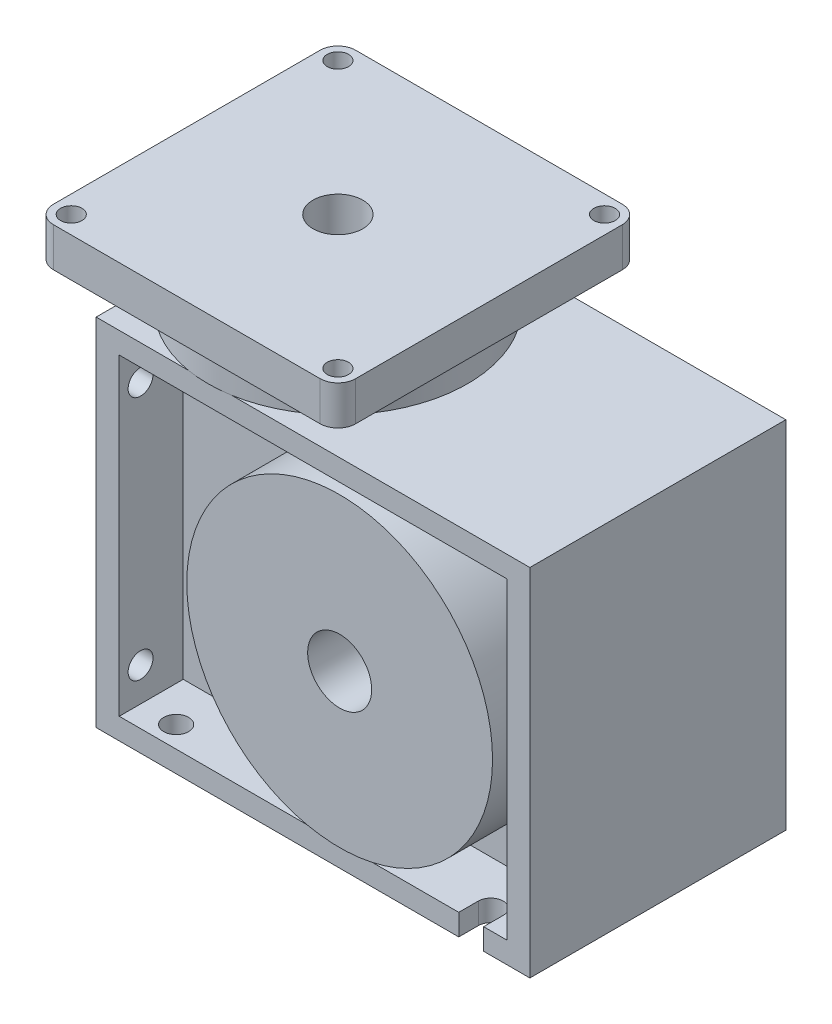
SolidWorks part; units mm, degrees
ref_plane "Alzado" through (0, 0, 0) normal (0, 0, 1) x (1, 0, 0)
ref_plane "Planta" through (0, 0, 0) normal (0, 1, 0) x (1, 0, 0)
ref_plane "Vista lateral" through (0, 0, 0) normal (1, 0, 0) x (0, 0, -1)
sketch "Croquis2" plane through (0, 0, 0) normal (0, 1, 0) x (1, 0, 0)
  line L1 (-61, 36) -> (61, 36)
  line L2 (-61, 36) -> (-61, -36)
  line L3 (-61, -36) -> (61, -36)
  line L4 (61, 36) -> (61, -36)
  point P0 (0, 0)
  dimension "D1" = 122
  dimension "D2" = 72
extrude "Saliente-Extruir1" add sketch "Croquis2" along normal blind 100
sketch "Croquis3" plane through (0, 0, -36) normal (0, 0, -1) x (-1, 0, 0)
  line L0 (-61, 50) -> (61, 50) construction
  line L1 (-61, 100) -> (-61, 0) construction
  line L2 (61, 100) -> (61, 0) construction
  line L3 (0, 100) -> (0, 0) construction
  line L4 (-61, 100) -> (61, 100) construction
  line L6 (-54.5, 6) -> (54.5, 6)
  line L7 (-54.5, 6) -> (-54.5, 94)
  line L8 (-54.5, 94) -> (54.5, 94)
  line L9 (54.5, 6) -> (54.5, 94)
  point P11 (0, 50)
  dimension "D1" = 88
  dimension "D2" = 109
extrude "Cortar-Extruir1" cut sketch "Croquis3" against normal blind 18 contours L7 L6 L9 L8
sketch "Croquis4" plane through (0, 0, 36) normal (0, 0, 1) x (1, 0, 0)
  line L0 (-61, 50) -> (61, 50) construction
  line L1 (-61, 100) -> (-61, 0) construction
  line L2 (61, 100) -> (61, 0) construction
  line L3 (0, 100) -> (0, 0) construction
  line L4 (-61, 100) -> (61, 100) construction
  line L6 (-54.5, 6) -> (54.5, 6)
  line L7 (-54.5, 6) -> (-54.5, 94)
  line L8 (-54.5, 94) -> (54.5, 94)
  line L9 (54.5, 6) -> (54.5, 94)
  point P11 (0, 50)
  dimension "D1" = 88
  dimension "D2" = 109
extrude "Cortar-Extruir2" cut sketch "Croquis4" against normal blind 18
sketch "Croquis5" plane through (0, 100, 0) normal (0, 1, 0) x (1, 0, 0)
  line L0 (-61, 0) -> (7.5, 0) construction
  line L1 (-61, 36) -> (-61, -36) construction
  line L3 (-61, 0) -> (-29, 0)
  circle A0 centre (-29, 0) radius 36.5
  line M3 (61, 36) -> (-61, 36)
  line M4 (-61, 36) -> (-61, -36)
  line M5 (-61, -36) -> (61, -36)
  dimension "D2" = 73
  dimension "D1" = 32
extrude "Saliente-Extruir2" add sketch "Croquis5" along normal blind 12 contours L3 L0 A0 M3 M4 | A0 M4 | L0 L3 A0 M4 M5 | A0 M5 | A0 M3
sketch "Croquis6" plane through (0, 112, 0) normal (0, 1, 0) x (1, 0, 0)
  line L0 (-65.5, 0) -> (7.5, 0) construction
  line L1 (-29, 36.5) -> (-29, -36.5) construction
  line L3 (-71.5, -42.5) -> (13.5, -42.5)
  line L4 (-71.5, -42.5) -> (-71.5, 42.5)
  line L5 (-71.5, 42.5) -> (13.5, 42.5)
  line L6 (13.5, -42.5) -> (13.5, 42.5)
  circle A0 centre (-29, 0) radius 36.5 construction
  arc A1 (-22.9792, -36) -> (-22.9792, 36) centre (-29, 0) ccw construction
  point P10 (-29, 0)
  dimension "D1" = 85
  dimension "D2" = 85
extrude "Saliente-Extruir3" add sketch "Croquis6" along normal blind 11
sketch "Croquis7" plane through (0, 0, 18) normal (0, 0, 1) x (1, 0, 0)
  line L0 (-54.5, 50) -> (-33.5, 50)
  line L1 (-54.5, 94) -> (-54.5, 6) construction
  circle A1 centre (9.5, 50) radius 43
  dimension "D2" = 86
  dimension "D1" = 21
extrude "Saliente-Extruir7" add sketch "Croquis7" along normal blind 20 contours A1
sketch "Croquis8" plane through (0, 0, -18) normal (0, 0, -1) x (-1, 0, 0)
  line L0 (54.5, 50) -> (33.5, 50)
  line L1 (54.5, 6) -> (54.5, 94) construction
  circle A0 centre (-9.5, 50) radius 43
  dimension "D2" = 86
  dimension "D1" = 21
extrude "Saliente-Extruir8" add sketch "Croquis8" along normal blind 20 contours A0
sketch "Croquis9" plane through (0, 0, 38) normal (0, 0, 1) x (1, 0, 0)
  circle A0 centre (9.5, 50) radius 9
  dimension "D1" = 18
extrude "Cortar-Extruir3" cut sketch "Croquis9" against normal up to surface (76 mm away) up to face at (-33.5, 50, -38)
sketch "Croquis10" plane through (0, 0, 0) normal (0, -1, 0) x (1, 0, 0)
  line L0 (-48, 30) -> (-61, 30)
  line L2 (-61, -36) -> (-61, 36) construction
  line L4 (-44.5, 33.5) -> (-44.5, 36)
  line L6 (-61, 36) -> (61, 36) construction
  line L7 (-48, -30) -> (-61, -30)
  line L9 (-44.5, -33.5) -> (-44.5, -36)
  line L10 (61, -36) -> (-61, -36) construction
  line L17 (48, 30.5) -> (61, 30.5)
  line L18 (61, 36) -> (61, -36) construction
  line L19 (48, -30.5) -> (61, -30.5)
  line L21 (41, -30.5) -> (41, -36)
  line L22 (48, -30.5) -> (48, -36)
  line L23 (48, -36) -> (41, -36)
  line L24 (41, 30.5) -> (41, 36)
  line L25 (48, 30.5) -> (48, 36)
  line L26 (41, 36) -> (48, 36)
  circle A4 centre (-44.5, 30) radius 3.5
  circle A5 centre (-44.5, -30) radius 3.5
  arc A6 (41, 30.5) -> (48, 30.5) centre (44.5, 30.5) ccw
  arc A7 (48, -30.5) -> (41, -30.5) centre (44.5, -30.5) ccw
  line M13 (61, 36) -> (-61, 36)
  line M15 (-61, -36) -> (61, -36)
  dimension "D1" = 7
  dimension "D2" = 13
  dimension "D3" = 2.5
  dimension "D6" = 2.5
  dimension "D4" = 7
  dimension "D7" = 7
  dimension "D9" = 7
  dimension "D5" = 13
  dimension "D8" = 13
  dimension "D10" = 13
extrude "Cortar-Extruir5" cut sketch "Croquis10" against normal up to surface (6 mm away) contours L24 A6 L25 M13 | L22 A7 L21 M15 | A5 | A4 up to face at (0, 6, 27)
sketch "Croquis11" plane through (-61, 0, 0) normal (-1, 0, 0) x (0, 0, 1)
  line L0 (-30, 88) -> (-30, 100)
  line L1 (-17.557, 100) -> (-36, 100) construction
  line L2 (-33.5, 84.5) -> (-36, 84.5)
  line L3 (-36, 100) -> (-36, 0) construction
  line L4 (33.5, 84.5) -> (36, 84.5)
  line L5 (36, 100) -> (36, 0) construction
  line L6 (30, 88) -> (30, 100)
  line L7 (36, 100) -> (17.557, 100) construction
  line L8 (-30, 12) -> (-30, 0)
  line L9 (-36, 0) -> (36, 0) construction
  line L10 (-33.5, 15.5) -> (-36, 15.5)
  line L11 (30, 12) -> (30, 0)
  line L12 (33.5, 15.5) -> (36, 15.5)
  circle A0 centre (-30, 84.5) radius 3.5
  circle A1 centre (30, 84.5) radius 3.5
  circle A2 centre (-30, 15.5) radius 3.5
  circle A3 centre (30, 15.5) radius 3.5
  dimension "D1" = 7
  dimension "D4" = 7
  dimension "D7" = 7
  dimension "D10" = 7
  dimension "D2" = 12
  dimension "D3" = 2.5
  dimension "D5" = 2.5
  dimension "D6" = 12
  dimension "D8" = 12
  dimension "D9" = 2.5
  dimension "D11" = 2.5
extrude "Cortar-Extruir6" cut sketch "Croquis11" against normal up to surface (6.5 mm away) contours A0 | A1 | A2 | A3 up to face at (-54.5, 50, -27)
sketch "Croquis12" plane through (0, 123, 0) normal (0, 1, 0) x (1, 0, 0)
  line L0 (-71.5, 0) -> (13.5, 0) construction
  line L1 (-71.5, 42.5) -> (-71.5, -42.5) construction
  line L2 (13.5, -42.5) -> (13.5, 42.5) construction
  circle A0 centre (-29, 0) radius 7
  dimension "D1" = 14
extrude "Cortar-Extruir7" cut sketch "Croquis12" against normal blind 36
sketch "Croquis13" plane through (0, 123, 0) normal (0, 1, 0) x (1, 0, 0)
  line L0 (-71.5, 42.5) -> (-61.5, 42.5)
  line L1 (13.5, 42.5) -> (-71.5, 42.5) construction
  line L2 (-61.5, 42.5) -> (-61.5, 32.5)
  line L3 (-61.5, 32.5) -> (-71.5, 32.5)
  line L4 (-71.5, 42.5) -> (-71.5, -42.5) construction
  line L5 (-71.5, 32.5) -> (-71.5, 42.5)
  line L6 (13.5, 42.5) -> (3.5, 42.5)
  line L7 (3.5, 42.5) -> (3.5, 32.5)
  line L8 (3.5, 32.5) -> (13.5, 32.5)
  line L9 (13.5, -42.5) -> (13.5, 42.5) construction
  line L10 (13.5, 32.5) -> (13.5, 42.5)
  line L11 (-71.5, -42.5) -> (-61.5, -42.5)
  line L12 (-71.5, -42.5) -> (13.5, -42.5) construction
  line L13 (-61.5, -42.5) -> (-61.5, -32.5)
  line L14 (-61.5, -32.5) -> (-71.5, -32.5)
  line L15 (-71.5, -32.5) -> (-71.5, -42.5)
  line L16 (13.5, -42.5) -> (3.5, -42.5)
  line L17 (3.5, -42.5) -> (3.5, -32.5)
  line L18 (3.5, -32.5) -> (13.5, -32.5)
  line L19 (13.5, -32.5) -> (13.5, -42.5)
  circle A0 centre (-66.5, 37.5) radius 3
  circle A1 centre (8.5, 37.5) radius 3
  circle A2 centre (-66.5, -37.5) radius 3
  circle A3 centre (8.5, -37.5) radius 3
  dimension "D9" = 6
  dimension "D10" = 6
  dimension "D11" = 6
  dimension "D12" = 6
  dimension "D1" = 10
  dimension "D2" = 10
  dimension "D3" = 10
  dimension "D4" = 10
  dimension "D5" = 10
  dimension "D6" = 10
  dimension "D7" = 10
  dimension "D8" = 10
extrude "Cortar-Extruir8" cut sketch "Croquis13" against normal up to surface (11 mm away) contours A0 | A1 | A2 | A3 up to face at (-29, 112, 36.5)
fillet "Redondeo2" radius 5 4 edges at (-71.5, 117.5, 42.5) (13.5, 117.5, 42.5) (13.5, 117.5, -42.5) (-71.5, 117.5, -42.5)
